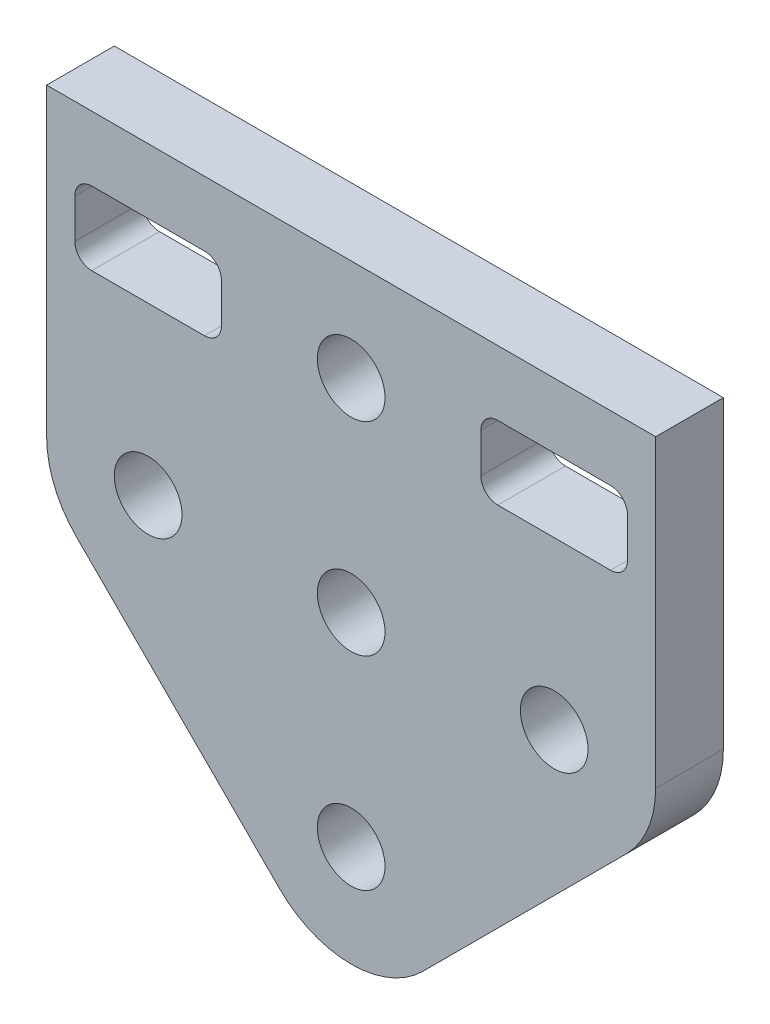
SolidWorks part; units mm, degrees
ref_plane "Alzado" through (0, 0, 0) normal (0, 0, 1) x (1, 0, 0)
ref_plane "Planta" through (0, 0, 0) normal (0, 1, 0) x (1, 0, 0)
ref_plane "Vista lateral" through (0, 0, 0) normal (1, 0, 0) x (0, 0, -1)
sketch "Model" plane through (0, 0, 0) normal (0, 0, 1) x (1, 0, 0)
  line L0 (174.2271, 213.1787) -> (174.2271, 204.1787)
  line L1 (201.2271, 217.6787) -> (174.2271, 217.6787)
  line L2 (174.2271, 213.1787) -> (174.2271, 217.6787)
  line L3 (201.2271, 217.6787) -> (201.2271, 204.1787)
  line L4 (190.909, 191.9967) -> (199.909, 200.9967)
  line L5 (184.5451, 191.9967) -> (175.5451, 200.9967)
  line L6 (193.4771, 214.0537) -> (193.4771, 212.3037)
  line L7 (194.2271, 211.5537) -> (199.2271, 211.5537)
  line L8 (199.9771, 212.3037) -> (199.9771, 214.0537)
  line L9 (199.2271, 214.8037) -> (194.2271, 214.8037)
  line L10 (175.4771, 214.0537) -> (175.4771, 212.3037)
  line L11 (176.2271, 211.5537) -> (181.2271, 211.5537)
  line L12 (181.9771, 212.3037) -> (181.9771, 214.0537)
  line L13 (181.2271, 214.8037) -> (176.2271, 214.8037)
  circle A0 centre (187.7271, 204.1787) radius 1.5
  circle A1 centre (178.7271, 204.1787) radius 1.5
  circle A2 centre (187.7271, 213.1787) radius 1.5
  circle A3 centre (187.7271, 195.1787) radius 1.5
  circle A4 centre (196.7271, 204.1787) radius 1.5
  arc A5 (184.5451, 191.9967) -> (190.909, 191.9967) centre (187.7271, 195.1787) ccw
  arc A6 (199.909, 200.9967) -> (201.2271, 204.1787) centre (196.7271, 204.1787) ccw
  arc A7 (174.2271, 204.1787) -> (175.5451, 200.9967) centre (178.7271, 204.1787) ccw
  arc A8 (194.2271, 214.8037) -> (193.4771, 214.0537) centre (194.2271, 214.0537) ccw
  arc A9 (193.4771, 212.3037) -> (194.2271, 211.5537) centre (194.2271, 212.3037) ccw
  arc A10 (199.2271, 211.5537) -> (199.9771, 212.3037) centre (199.2271, 212.3037) ccw
  arc A11 (199.9771, 214.0537) -> (199.2271, 214.8037) centre (199.2271, 214.0537) ccw
  arc A12 (176.2271, 214.8037) -> (175.4771, 214.0537) centre (176.2271, 214.0537) ccw
  arc A13 (175.4771, 212.3037) -> (176.2271, 211.5537) centre (176.2271, 212.3037) ccw
  arc A14 (181.2271, 211.5537) -> (181.9771, 212.3037) centre (181.2271, 212.3037) ccw
  arc A15 (181.9771, 214.0537) -> (181.2271, 214.8037) centre (181.2271, 214.0537) ccw
extrude "Saliente-Extruir1" add sketch "Model" along normal blind 3
